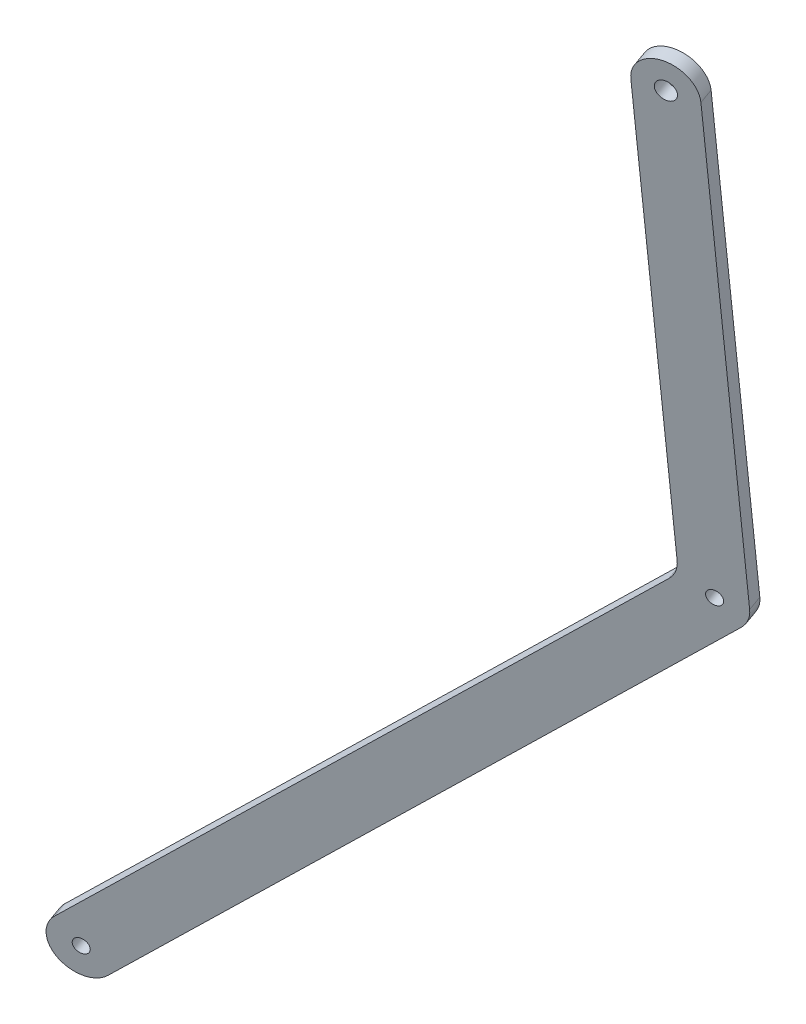
SolidWorks part; units mm, degrees
ref_plane "Front Plane" through (0, 0, 0) normal (0, 0, 1) x (1, 0, 0)
ref_plane "Top Plane" through (0, 0, 0) normal (0, 1, 0) x (1, 0, 0)
ref_plane "Right Plane" through (0, 0, 0) normal (1, 0, 0) x (0, 0, -1)
sketch3d "3DSketch1"
  line L0 (0, 0, 0) -> (250.6651, 243.9369, -29.3318)
  line L1 (250.6651, 243.9369, -29.3318) -> (258.4526, 456.6191, 0)
ref_plane "Plane1" through (0, 0, 0) normal (0.2496, -0.1413, 0.958) x (0.9684, 0.0364, -0.2469)
sketch "Sketch2" plane through (0, 0, 0) normal (0.2496, -0.1413, 0.958) x (0.9684, 0.0364, -0.2469)
  line L0 (-8.5771, 9.3661) -> (250.2789, 246.4149)
  line L1 (267.4331, 227.6826) -> (8.5771, -9.3661)
  line L2 (271.5471, 236.5733) -> (279.5891, 451.2592)
  line L3 (254.2069, 452.21) -> (246.1649, 237.5241)
  circle A0 centre (0, 0) radius 3.2639
  circle A1 centre (258.856, 237.0487) radius 3.2639
  circle A2 centre (266.898, 451.7346) radius 4.1999
  circle A3 centre (0, 0) radius 12.7
  circle A4 centre (258.856, 237.0487) radius 12.7
  circle A5 centre (266.898, 451.7346) radius 12.7
  arc A6 (242.4483, 239.2439) -> (246.5624, 248.1346) centre (233.8713, 248.61) ccw
  dimension "D1" = 6.5278
  dimension "D2" = 8.3998
  dimension "D3" = 25.4
extrude "Boss-Extrude1" add sketch "Sketch2" along normal mid plane 6.35 contours A4 L3 L0 A3 L1 | A3 A0 | A4 A1 | A5 L3 L0 A4 L2 | A4 L0 L3 | A5 A2 | A6 L0 L3
